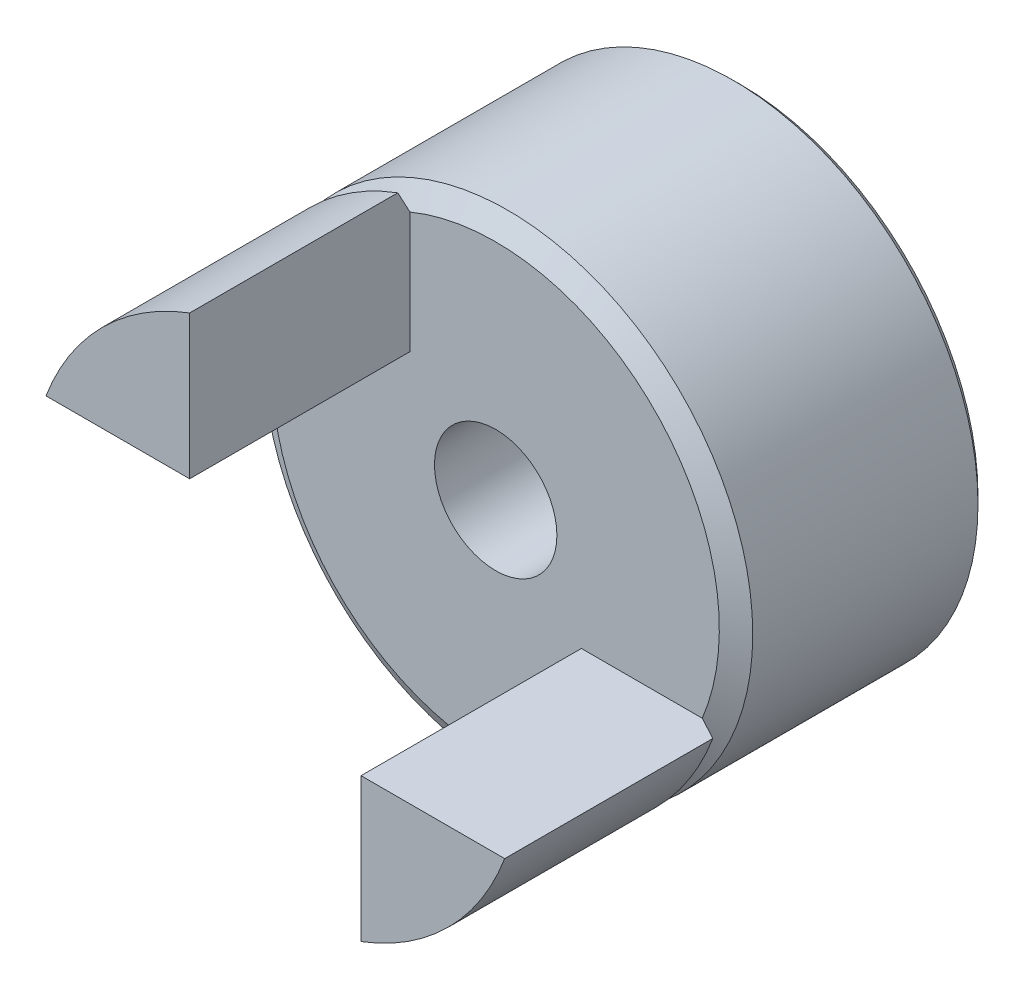
SolidWorks part; units mm, degrees
ref_plane "정면" through (0, 0, 0) normal (0, 0, 1) x (1, 0, 0)
ref_plane "윗면" through (0, 0, 0) normal (0, 1, 0) x (1, 0, 0)
ref_plane "우측면" through (0, 0, 0) normal (1, 0, 0) x (0, 0, -1)
sketch "스케치1" plane through (0, 0, 0) normal (0, 0, 1) x (1, 0, 0)
  circle A0 centre (0, 0) radius 10
  circle A1 centre (0, 0) radius 2.5
  dimension "D1" = 5
  dimension "D2" = 20
extrude "보스-돌출1" add sketch "스케치1" along normal blind 10
chamfer "모따기1" distance 0.3 angle 45 2 edges at (2.5, 0, 0) (10, 0, 0)
sketch "스케치2" plane through (0, 0, 10) normal (0, 0, 1) x (1, 0, 0)
  line L1 (-10, -3.5) -> (10, -3.5)
  line L2 (-10, -3.5) -> (-10, 3.5)
  line L3 (-10, 3.5) -> (10, 3.5)
  line L4 (10, -3.5) -> (10, 3.5)
  line L5 (-10, -3.5) -> (10, 3.5) construction
  line L6 (-10, 3.5) -> (10, -3.5) construction
  line L7 (-3.5, -10) -> (3.5, -10)
  line L8 (-3.5, -10) -> (-3.5, 10)
  line L9 (-3.5, 10) -> (3.5, 10)
  line L10 (3.5, -10) -> (3.5, 10)
  line L11 (-3.5, -10) -> (3.5, 10) construction
  line L12 (-3.5, 10) -> (3.5, -10) construction
  circle A1 centre (0, 0) radius 10
  circle A2 centre (0, 0) radius 10
  circle M5 centre (0, 0) radius 10
  dimension "D2" = 7
  dimension "D1" = 0
extrude "보스-돌출2" add sketch "스케치2" along normal blind 9 contours L3 L8 M5 | L10 L1 M5
sketch "스케치3" plane through (0, 0, 0) normal (0, 1, 0) x (1, 0, 0)
  line L1 (9.134, -10) -> (10, -10.5)
  line L2 (10, -10.5) -> (10, -9.5)
  line L3 (10, -9.5) -> (9.134, -10)
  line L7 (0, 0) -> (0, -17.4659) construction
  circle A0 centre (9.7113, -10) radius 0.2887 construction
  dimension "D1" = 10
  dimension "D2" = 1
  dimension "D3" = 9.5
revolve "컷-회전1" cut sketch "스케치3" angle 360 about L7
